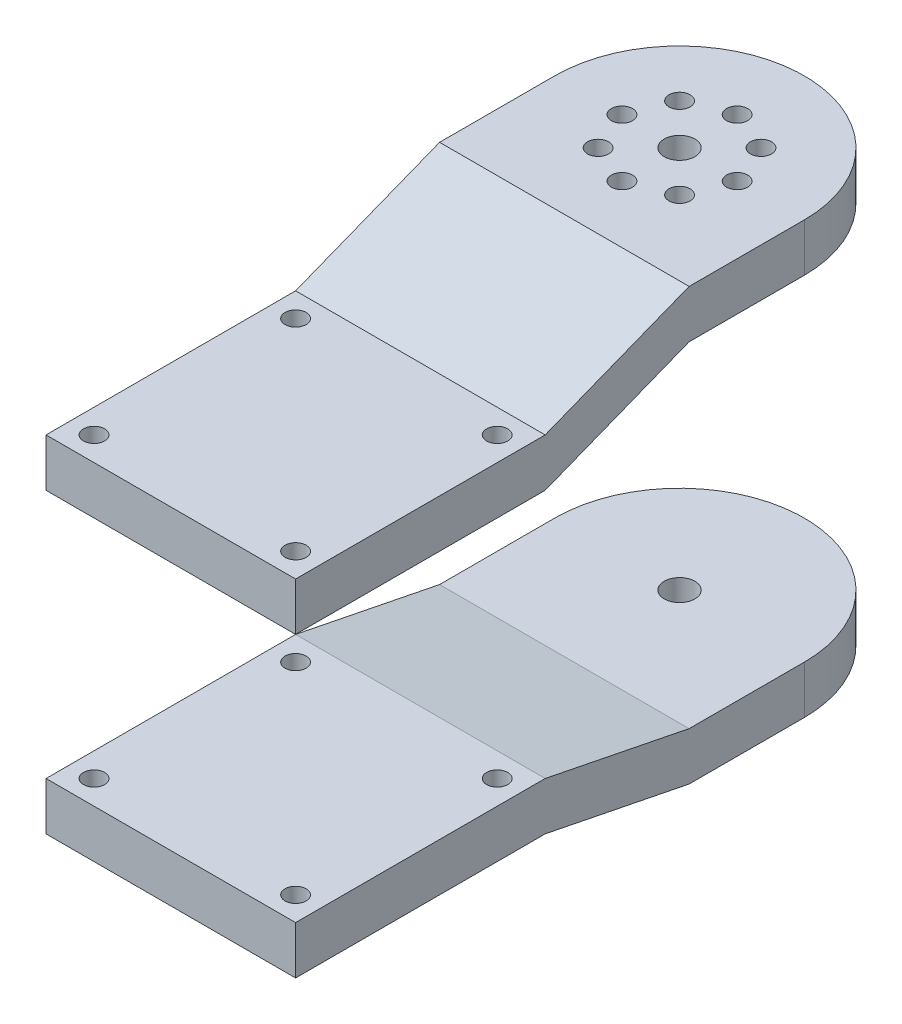
SolidWorks part; units mm, degrees
material "ABS"
ref_plane "正面" through (0, 0, 0) normal (0, 0, 1) x (1, 0, 0)
ref_plane "平面" through (0, 0, 0) normal (0, 1, 0) x (1, 0, 0)
ref_plane "右側面" through (0, 0, 0) normal (1, 0, 0) x (0, 0, -1)
sketch "ｽｹｯﾁ1" plane through (0, 0, 0) normal (0, 1, 0) x (1, 0, 0)
  line L0 (-13, 40) -> (-13, -13)
  line L1 (-10.5, 10.5) -> (10.5, 10.5) construction
  line L2 (-10.5, 10.5) -> (-10.5, -10.5) construction
  line L3 (-10.5, -10.5) -> (10.5, -10.5) construction
  line L4 (10.5, 10.5) -> (10.5, -10.5) construction
  line L5 (-10.5, 10.5) -> (10.5, -10.5) construction
  line L6 (-10.5, -10.5) -> (10.5, 10.5) construction
  line L7 (-13, -13) -> (13, -13)
  line L8 (13, -13) -> (13, 40)
  circle A0 centre (-10.5, 10.5) radius 1.1
  circle A1 centre (-10.5, -10.5) radius 1.1
  circle A2 centre (10.5, -10.5) radius 1.1
  circle A3 centre (10.5, 10.5) radius 1.1
  arc A4 (13, 40) -> (-13, 40) centre (0, 40) ccw
  circle A5 centre (0, 40) radius 6 construction
  circle A6 centre (0, 46) radius 1.1
  circle A7 centre (4.2426, 44.2426) radius 1.1
  circle A8 centre (6, 40) radius 1.1
  circle A9 centre (4.2426, 35.7574) radius 1.1
  circle A10 centre (0, 34) radius 1.1
  circle A11 centre (-4.2426, 35.7574) radius 1.1
  circle A12 centre (-6, 40) radius 1.1
  circle A13 centre (-4.2426, 44.2426) radius 1.1
  circle A14 centre (0, 40) radius 1.6
  point P0 (0, 0)
  point P35 (0, 40)
  dimension "D2" = 2.2
  dimension "D3" = 2.2
  dimension "D4" = 2.2
  dimension "D5" = 2.2
  dimension "D9" = 40
  dimension "D10" = 12
  dimension "D11" = 2.2
  dimension "D13" = 3.2
  dimension "D1" = 21
  dimension "D6" = 13
  dimension "D7" = 13
  dimension "D8" = 13
  dimension "D12" = 8
extrude "ﾎﾞｽ - 押し出し1" add sketch "ｽｹｯﾁ1" along normal blind 5
ref_plane "平面1" through (0, -34.9, 0) normal (0, 1, 0) x (1, 0, 0)
sketch "ｽｹｯﾁ2" plane through (0, -34.9, 0) normal (0, 1, 0) x (1, 0, 0)
  line L3 (13, -13) -> (13, 40)
  line L4 (-13, -13) -> (13, -13)
  line L5 (-13, 40) -> (-13, -13)
  line L6 (13, -13) -> (13, 40)
  line L7 (-13, -13) -> (13, -13)
  line L8 (-13, 40) -> (-13, -13)
  circle A0 centre (0, 40) radius 1.6
  arc A1 (13, 40) -> (-13, 40) centre (0, 40) ccw
  arc A2 (13, 40) -> (-13, 40) centre (0, 40) ccw
  circle A3 centre (10.5, -10.5) radius 1.1 construction
  circle A4 centre (-10.5, -10.5) radius 1.1 construction
  circle A5 centre (-10.5, 10.5) radius 1.1 construction
  circle A6 centre (10.5, 10.5) radius 1.1 construction
  circle A7 centre (10.5, -10.5) radius 1.1
  circle A8 centre (-10.5, -10.5) radius 1.1
  circle A9 centre (-10.5, 10.5) radius 1.1
  circle A10 centre (10.5, 10.5) radius 1.1
  dimension "D2" = 3.2
  dimension "D1" = 0
extrude "ﾎﾞｽ - 押し出し2" add sketch "ｽｹｯﾁ2" against normal blind 5 separate body
sketch "ｽｹｯﾁ4" plane through (0, 0, 0) normal (0, 1, 0) x (1, 0, 0)
  line L0 (-13, 40) -> (-13, -13) construction
  line L1 (13, -13) -> (-13, -13)
  line L2 (13, -13) -> (13, 13)
  line L3 (13, 13) -> (-13, 13)
  line L4 (-13, -13) -> (-13, 13)
  circle A0 centre (10.5, -10.5) radius 1.1 construction
  circle A1 centre (-10.5, -10.5) radius 1.1 construction
  circle A2 centre (-10.5, 10.5) radius 1.1 construction
  circle A3 centre (10.5, 10.5) radius 1.1 construction
  circle A4 centre (10.5, -10.5) radius 1.1
  circle A5 centre (-10.5, -10.5) radius 1.1
  circle A6 centre (-10.5, 10.5) radius 1.1
  circle A7 centre (10.5, 10.5) radius 1.1
  dimension "D1" = 26
extrude "ﾎﾞｽ - 押し出し3" add sketch "ｽｹｯﾁ4" against normal blind 5.9
sketch "ｽｹｯﾁ5" plane through (0, -34.9, 0) normal (0, 1, 0) x (1, 0, 0)
  line L0 (13, -13) -> (13, 40) construction
  line L1 (-13, -13) -> (13, -13)
  line L2 (-13, -13) -> (-13, 13)
  line L3 (-13, 13) -> (13, 13)
  line L4 (13, -13) -> (13, 13)
  circle A0 centre (10.5, -10.5) radius 1.1 construction
  circle A1 centre (-10.5, -10.5) radius 1.1 construction
  circle A2 centre (-10.5, 10.5) radius 1.1 construction
  circle A3 centre (10.5, 10.5) radius 1.1 construction
  circle A4 centre (10.5, -10.5) radius 1.1
  circle A5 centre (-10.5, -10.5) radius 1.1
  circle A6 centre (-10.5, 10.5) radius 1.1
  circle A7 centre (10.5, 10.5) radius 1.1
  dimension "D1" = 26
extrude "ﾎﾞｽ - 押し出し4" add sketch "ｽｹｯﾁ5" along normal blind 3
sketch "ｽｹｯﾁ6" plane through (13, 0, 0) normal (1, 0, 0) x (0, 0, -1)
  line L0 (28, 0) -> (13, -5.9)
  line L1 (13, -5.9) -> (13, 0)
  line L2 (13, -5.9) -> (13, 0) construction
  line L3 (13, 0) -> (28, 0)
  line L4 (13, 0) -> (40, 0) construction
  line L5 (13, -31.9) -> (13, -34.9)
  line L6 (13, -34.9) -> (28, -34.9)
  line L7 (13, -34.9) -> (40, -34.9) construction
  line L8 (28, -34.9) -> (13, -31.9)
  dimension "D1" = 15
extrude "ﾎﾞｽ - 押し出し5" add sketch "ｽｹｯﾁ6" against normal up to surface (26 mm away) up to face at (-13, -0.3, -13.3333)
sketch "ｽｹｯﾁ7" plane through (13, 0, 0) normal (1, 0, 0) x (0, 0, -1)
  line L0 (28, 5) -> (13, -0.9)
  line L1 (-13, 5) -> (40, 5) construction
  line L2 (13, -0.9) -> (-13, -0.9)
  line L3 (-13, -0.9) -> (-13, 5)
  line L4 (-13, 5) -> (28, 5)
  line L7 (13, -5.9) -> (28, 0) construction
  line L8 (28, -39.9) -> (-13, -39.9)
  line L9 (-13, -39.9) -> (40, -39.9) construction
  line L10 (-13, -39.9) -> (-13, -36.9)
  line L11 (-13, -39.9) -> (-13, -31.9) construction
  line L12 (-13, -36.9) -> (13, -36.9)
  line L13 (13, -36.9) -> (28, -39.9)
  point P4 (0, 0)
  point P23 (0, 0)
  point P28 (0, 0)
  dimension "D1" = 3
extrude "ｶｯﾄ - 押し出し1" cut sketch "ｽｹｯﾁ7" against normal through all
